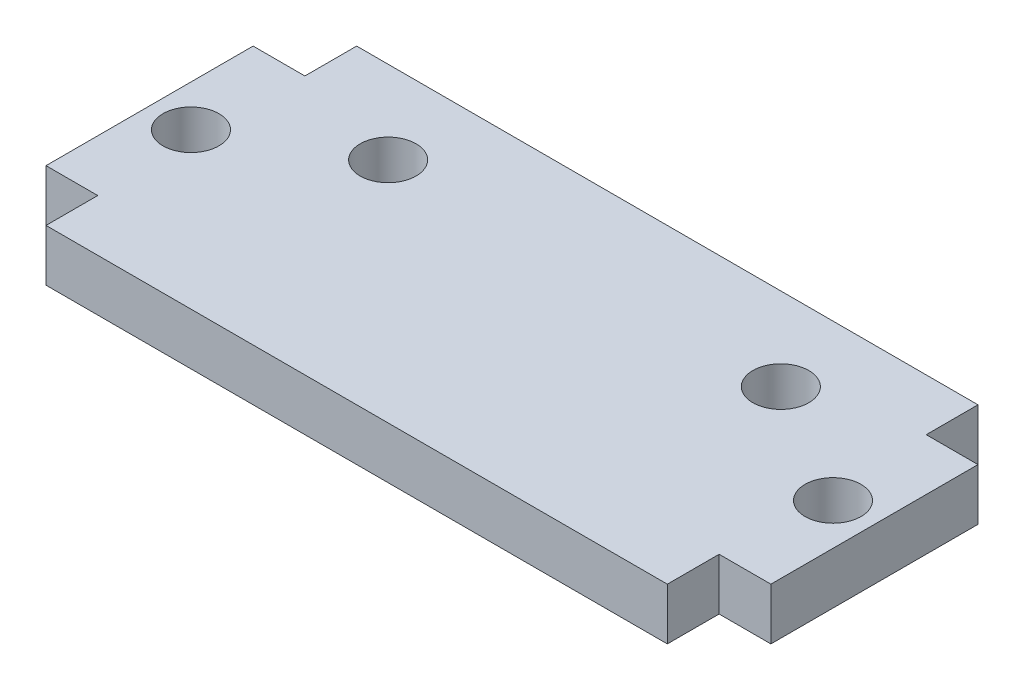
SolidWorks part; units mm, degrees
ref_plane "Front Plane" through (0, 0, 0) normal (0, 0, 1) x (1, 0, 0)
ref_plane "Top Plane" through (0, 0, 0) normal (0, 1, 0) x (1, 0, 0)
ref_plane "Right Plane" through (0, 0, 0) normal (1, 0, 0) x (0, 0, -1)
sketch "Sketch1" plane through (0, 0, 0) normal (0, 1, 0) x (1, 0, 0)
  line L0 (19.05, 0) -> (-19.05, 0)
  line L1 (-19.05, 0) -> (-19.05, 3.175)
  line L2 (-19.05, 3.175) -> (-22.225, 3.175)
  line L3 (-22.225, 3.175) -> (-22.225, 15.875)
  line L4 (-22.225, 15.875) -> (-19.05, 15.875)
  line L5 (-19.05, 15.875) -> (-19.05, 19.05)
  line L6 (-19.05, 19.05) -> (19.05, 19.05)
  line L7 (0, 19.05) -> (0, 0) construction
  line L8 (-22.225, 9.525) -> (-19.685, 9.525) construction
  line L9 (22.225, 9.525) -> (19.685, 9.525) construction
  line L10 (19.05, 15.875) -> (19.05, 19.05)
  line L11 (22.225, 15.875) -> (19.05, 15.875)
  line L12 (22.225, 3.175) -> (22.225, 15.875)
  line L13 (19.05, 3.175) -> (22.225, 3.175)
  line L14 (19.05, 0) -> (19.05, 3.175)
  line L15 (-22.225, 9.525) -> (22.225, 9.525) construction
  line L16 (-22.225, 13.97) -> (22.225, 13.97) construction
  circle A0 centre (-19.685, 9.525) radius 1.7145
  circle A1 centre (19.685, 9.525) radius 1.7145
  circle A2 centre (-12.0396, 13.97) radius 1.7145
  circle A3 centre (12.0396, 13.97) radius 1.7145
  dimension "D7" = 3.429
  dimension "D8" = 3.429
  dimension "D1" = 3.175
  dimension "D2" = 12.7
  dimension "D3" = 3.175
  dimension "D4" = 3.175
  dimension "D5" = 22.225
  dimension "D6" = 2.54
  dimension "D9" = 12.0396
  dimension "D10" = 4.445
extrude "Boss-Extrude2" add sketch "Sketch1" along normal blind 3.175
